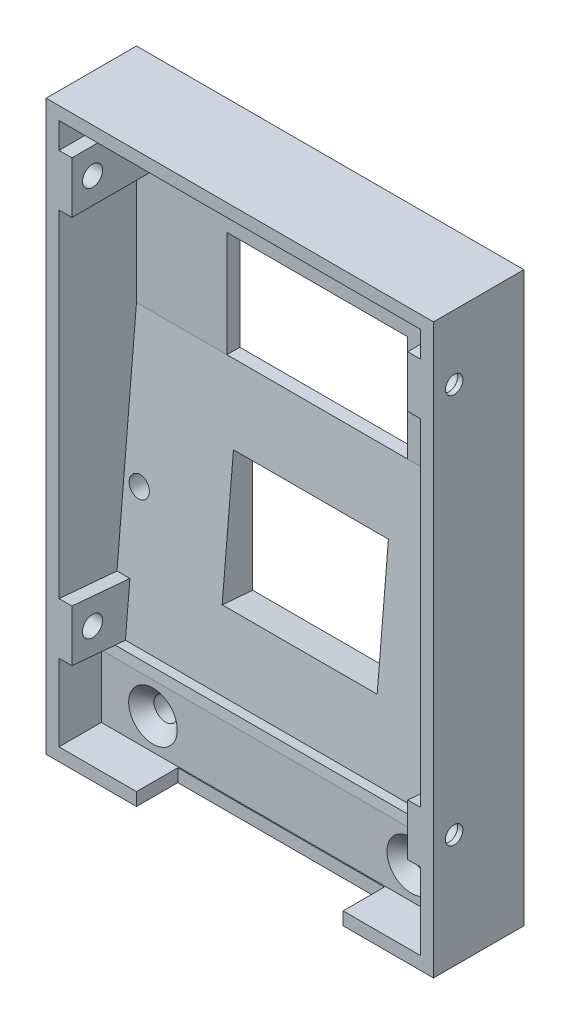
SolidWorks part; units mm, degrees
ref_plane "Přední rovina" through (0, 0, 0) normal (0, 0, 1) x (1, 0, 0)
ref_plane "Horní rovina" through (0, 0, 0) normal (0, 1, 0) x (1, 0, 0)
ref_plane "Pravá rovina" through (0, 0, 0) normal (1, 0, 0) x (0, 0, -1)
sketch "Skica1" plane through (0, 0, 0) normal (0, 0, 1) x (1, 0, 0)
  line L0 (-17.5, 35) -> (-17.5, -35)
  line L1 (-37.5, 55) -> (37.5, 55)
  line L2 (-37.5, 55) -> (-37.5, -55)
  line L3 (-37.5, -55) -> (37.5, -55)
  line L4 (37.5, 55) -> (37.5, -55)
  line L5 (-37.5, 55) -> (37.5, -55) construction
  line L6 (-37.5, -55) -> (37.5, 55) construction
  line L7 (-17.5, -35) -> (17.5, -35)
  line L8 (17.5, 35) -> (17.5, -35)
  line L9 (-17.5, 35) -> (17.5, 35)
  point P0 (0, 0)
  dimension "D1" = 75
  dimension "D2" = 110
  dimension "D3" = 20
extrude "Přidat vysunutím1" add sketch "Skica1" along normal blind 2.5
sketch "Skica2" plane through (0, 0, 2.5) normal (0, 0, 1) x (1, 0, 0)
  line L0 (-35, -52.5) -> (35, -52.5)
  line L1 (-37.5, 55) -> (37.5, 55)
  line L2 (-37.5, 55) -> (-37.5, -55)
  line L3 (-37.5, -55) -> (37.5, -55)
  line L4 (37.5, 55) -> (37.5, -55)
  line L5 (-37.5, 55) -> (37.5, -55) construction
  line L6 (-37.5, -55) -> (37.5, 55) construction
  line L7 (35, 52.5) -> (35, -52.5)
  line L8 (-35, 52.5) -> (35, 52.5)
  line L9 (-35, 52.5) -> (-35, -52.5)
  point P0 (0, 0)
  dimension "D1" = 2.5
extrude "Přidat vysunutím2" add sketch "Skica2" along normal blind 15
sketch "Skica3" plane through (35, 0, 0) normal (-1, 0, 0) x (0, 0, 1)
  line L0 (2.5, -52.5) -> (2.5, 14.5)
  line L1 (2.5, -52.5) -> (2.5, 52.5) construction
  line L2 (2.5, 14.5) -> (8.3617, -52.5)
  line L3 (17.5, -52.5) -> (2.5, -52.5) construction
  line L4 (8.3617, -52.5) -> (2.5, -52.5)
  dimension "D1" = 67
  dimension "D2" = 5
extrude "Přidat vysunutím3" add sketch "Skica3" along normal up to next
sketch "Skica4" plane through (0, 0, 2.5) normal (0, 0, -1) x (-1, 0, 0)
  line L0 (-17.5, 14.5) -> (17.5, 14.5)
  line L1 (17.5, 14.5) -> (17.5, -35)
  line L2 (17.5, -35) -> (-17.5, -35)
  line L3 (-17.5, -35) -> (-17.5, 14.5)
extrude "Přidat vysunutím4" add sketch "Skica4" along normal up to surface (2.5 mm away) up to face at (0, 0, 0)
sketch "Skica5" plane through (0, 0.3272, 3.74) normal (0, 0.0872, 0.9962) x (1, 0, 0)
  line L0 (35, -41.029) -> (-35, -41.029)
  line L1 (35, -53.029) -> (35, 14.2269) construction
  line L2 (-35, 14.2269) -> (-35, -53.029) construction
  line L4 (35, -41.029) -> (-35, -41.029)
  line L5 (35, -41.029) -> (35, -39.029)
  line L6 (35, -39.029) -> (-35, -39.029)
  line L7 (-35, -41.029) -> (-35, -39.029)
  line M3 (-35, 14.2269) -> (-35, -53.029)
  line M5 (35, -53.029) -> (35, 14.2269)
  dimension "D1" = 12
  dimension "D2" = 2
extrude "Přidat vysunutím5" add sketch "Skica5" along normal blind 2 contours L6 L0 M5 M3
ref_plane "Rovina1" through (0, 0, 8.75) normal (0, 0, -1) x (-1, 0, 0)
sketch "Skica7" plane through (35, 0, 0) normal (-1, 0, 0) x (0, 0, 1)
  line L0 (9.3083, -52.5) -> (9.3083, 14.5)
  line L1 (17.5, -52.5) -> (8.3617, -52.5) construction
  line L2 (9.3083, 14.5) -> (2.5, 14.5)
  line L3 (2.5, 14.5) -> (8.3617, -52.5)
  line L4 (8.3617, -52.5) -> (9.3083, -52.5)
ref_plane "Rovina2" through (0, 0, 0) normal (1, 0, 0) x (0, 0, -1)
sketch "Skica9" plane through (35, 0, 0) normal (-1, 0, 0) x (0, 0, 1)
  line L0 (9.3083, -52.5) -> (9.3083, -40.3714)
  line L1 (9.3083, -40.3714) -> (7.3159, -40.5457)
  line L2 (7.3159, -40.5457) -> (8.3617, -52.5)
  line L3 (8.3617, -52.5) -> (9.3083, -52.5)
extrude "Přidat vysunutím7" add sketch "Skica9" along normal through all
sketch "Skica10" plane through (0, 0, 9.3083) normal (0, 0, 1) x (1, 0, 0)
  line L0 (35, -52.5) -> (35, -40.3714)
  line L1 (35, -40.3714) -> (35, -46.4357)
  line L2 (35, -46.4357) -> (-35, -46.4357)
  line L3 (-35, -52.5) -> (-35, -40.3714) construction
  point P4 (25, -46.4357)
  point P9 (-25, -46.4357)
  dimension "D1" = 10
  dimension "D2" = 10
hole_wizard "Kuželové zahloubení pro M4 šroubu se zápustnou hlavou plochou1" positions "Skica11" profile "Skica12" countersink size "M4" standard "DIN" end condition through all
sketch "Skica11" plane through (0, 0, 9.3083) normal (0, 0, 1) x (1, 0, 0)
  point P0 (25, -46.4357)
  point P3 (-25, -46.4357)
sketch "Skica12" plane through (25, -46.4357, 9.3083) normal (1, 0, 0) x (0, -1, 0)
  line L0 (0, 0) -> (0, 9.3083)
  line L1 (0, 9.3083) -> (2.25, 9.3083)
  line L2 (2.25, 9.3083) -> (2.25, 2.45)
  line L3 (2.25, 2.45) -> (4.7, 0)
  line L5 (4.7, 0) -> (0, 0)
  line L6 (-2.25, 2.45) -> (-4.7, 0) construction
  line L11 (0, -6.35) -> (0, 107.95) construction
  dimension "Průměr díry skrz" = 4.5
  dimension "Hloubka díry skrz" = 9.3083
  dimension "Průměr blíz. kuž. zahloubení" = 9.4
  dimension "Úhel blíz. kuž. zahloubení" = 90
sketch "Skica13" plane through (0, 0, 2.5) normal (0, 0, 1) x (1, 0, 0)
  line L0 (-35, 42.5) -> (35, 42.5)
  line L1 (-35, 52.5) -> (-35, 14.5) construction
  line L2 (35, 14.5) -> (35, 52.5) construction
  point P6 (25, 42.5)
  point P7 (-25, 42.5)
  dimension "D1" = 10
  dimension "D2" = 10
  dimension "D3" = 10
hole_wizard "Kuželové zahloubení pro M4 šroubu se zápustnou hlavou plochou2" positions "Skica14" profile "Skica15" countersink size "M4" standard "DIN" end condition through all
sketch "Skica14" plane through (0, 0, 2.5) normal (0, 0, 1) x (1, 0, 0)
  point P0 (25, 42.5)
  point P3 (-25, 42.5)
sketch "Skica15" plane through (25, 42.5, 2.5) normal (1, 0, 0) x (0, -1, 0)
  line L0 (0, 0) -> (0, 2.5)
  line L1 (0, 2.5) -> (2.25, 2.5)
  line L2 (2.25, 2.5) -> (2.25, 2.45)
  line L3 (2.25, 2.45) -> (4.7, 0)
  line L5 (4.7, 0) -> (0, 0)
  line L6 (-2.25, 2.45) -> (-4.7, 0) construction
  line L11 (0, -6.35) -> (0, 107.95) construction
  dimension "Průměr díry skrz" = 4.5
  dimension "Hloubka díry skrz" = 2.5
  dimension "Průměr blíz. kuž. zahloubení" = 9.4
  dimension "Úhel blíz. kuž. zahloubení" = 90
sketch "Skica16" plane through (0, 0.3272, 3.74) normal (0, 0.0872, 0.9962) x (1, 0, 0)
  line L0 (35, -14.029) -> (-35, -14.029)
  line L1 (35, -39.029) -> (35, 14.2269) construction
  line L2 (-35, 14.2269) -> (-35, -39.029) construction
  point P6 (32, -14.029)
  point P7 (-32, -14.029)
  dimension "D1" = 25
  dimension "D2" = 3
  dimension "D3" = 3
hole_wizard "Díry pro kolík, velikost mm1" positions "Skica17" profile "Skica18" hole size "Ø4.0" standard "DIN"
sketch "Skica17" plane through (0, 0.3272, 3.74) normal (0, 0.0872, 0.9962) x (1, 0, 0)
  point P0 (32, -14.029)
  point P3 (-32, -14.029)
sketch "Skica18" plane through (32, -13.6484, 4.9627) normal (1, 0, 0) x (0, -0.9962, 0.0872)
  line L0 (0, 0) -> (0, 4)
  line L1 (0, 4) -> (1.95, 4)
  line L2 (1.95, 4) -> (1.95, 0)
  line L5 (1.95, 0) -> (0, 0)
  line L10 (0, 4) -> (-1.95, 4) construction
  line L11 (0, -6.35) -> (0, 107.95) construction
  dimension "Průměr díry" = 3.9
  dimension "Hloubka díry" = 4
  dimension "Úhel vrtání" = 180
sketch "Skica19" plane through (0, 0.3272, 3.74) normal (0, 0.0872, 0.9962) x (1, 0, 0)
  line L0 (0, 14.2269) -> (0, -39.029)
  line L1 (-17.5, 14.2269) -> (17.5, 14.2269) construction
  line L2 (35, -39.029) -> (-35, -39.029) construction
  line L4 (15, -24.901) -> (-15, -24.901)
  line L5 (15, -24.901) -> (15, 0.099)
  line L6 (15, 0.099) -> (-15, 0.099)
  line L7 (-15, -24.901) -> (-15, 0.099)
  line L8 (15, -24.901) -> (-15, 0.099) construction
  line L9 (15, 0.099) -> (-15, -24.901) construction
  point P6 (0, -12.401)
  dimension "D1" = 30
  dimension "D2" = 25
extrude "Odebrat vysunutím1" cut sketch "Skica19" against normal through all contours L5 L6 L7 L4
sketch "Skica20" plane through (0, -55, 0) normal (0, -1, 0) x (1, 0, 0)
  line L3 (0, 9.5) -> (-20, 9.5)
  line L4 (-20, 9.5) -> (-20, 17.5)
  line L5 (0, 9.5) -> (20, 9.5)
  line L6 (20, 9.5) -> (20, 17.5)
  line L7 (-20, 17.5) -> (20, 17.5)
  line L10 (-37.5, 17.5) -> (37.5, 17.5) construction
  line L11 (-20, 17.5) -> (20, 17.5)
  point P6 (0, 9.5)
  dimension "D1" = 20
  dimension "D2" = 20
  dimension "D3" = 9.5
extrude "Odebrat vysunutím4" cut sketch "Skica20" against normal blind 10
sketch "Skica21" plane through (-35, 0, 0) normal (1, 0, 0) x (0, 0, -1)
  line L0 (-7.1416, -38.5533) -> (-6.2733, -28.6292)
  line L1 (-2.5, 14.5) -> (-7.1416, -38.5533) construction
  line L2 (-6.2733, -28.6292) -> (-17.5, -27.647)
  line L3 (-17.5, 52.5) -> (-17.5, -52.5) construction
  line L4 (-17.5, -27.647) -> (-17.5, -37.647)
  line L5 (-17.5, -37.647) -> (-7.1416, -38.5533)
  line L6 (-2.5, 52.5) -> (-2.5, 14.5) construction
  line L7 (-17.5, 47.5) -> (-2.5, 47.5)
  line L8 (-17.5, 47.5) -> (-17.5, 37.5)
  line L9 (-17.5, 37.5) -> (-2.5, 37.5)
  line L10 (-2.5, 47.5) -> (-2.5, 37.5)
  dimension "D1" = 10
  dimension "D2" = 5
  dimension "D3" = 10
extrude "Přidat vysunutím8" add sketch "Skica21" along normal blind 2.5
mirror "Zrcadlit1" about plane through (0, 0, 0) normal (1, 0, 0) of "Přidat vysunutím8"
sketch "Skica22" plane through (-32.5, 0, 0) normal (1, 0, 0) x (0, 0, -1)
  line L0 (-17.5, -32.647) -> (-6.7074, -33.5913)
  line L1 (-17.5, -27.647) -> (-17.5, -37.647) construction
  line L2 (-7.1416, -38.5533) -> (-6.2733, -28.6292) construction
  line L3 (-17.5, 42.5) -> (-2.5, 42.5)
  line L4 (-17.5, 47.5) -> (-17.5, 37.5) construction
  line L5 (-2.5, 37.5) -> (-2.5, 47.5) construction
  point P6 (-13.5152, -32.9957)
  point P13 (-13.5, 42.5)
  dimension "D1" = 4
  dimension "D2" = 4
hole_wizard "Válcové zahloubení pro M3 šrouby s vnitřním šestihranem1" positions "Skica23" profile "Skica24" counterbore size "M3" standard "DIN"
sketch "Skica23" plane through (-32.5, 0, 0) normal (1, 0, 0) x (0, 0, -1)
  point P0 (-13.5, 42.5)
  point P3 (-13.5152, -32.9957)
sketch "Skica24" plane through (-32.5, 42.5, 13.5) normal (0, 1, 0) x (0, 0, -1)
  line L0 (0, 0) -> (0, 5)
  line L1 (0, 5) -> (1.7, 5)
  line L3 (1.7, 5) -> (1.7, 4)
  line L4 (1.7, 4) -> (1.95, 4)
  line L5 (1.95, 4) -> (1.95, 0)
  line L7 (1.95, 0) -> (0, 0)
  line L11 (0, -6.35) -> (0, 107.95) construction
  dimension "Průměr díry skrz" = 3.4
  dimension "Hloubka díry skrz" = 5
  dimension "Průměr válcového zahloubení" = 3.9
  dimension "Hloubka válcového zahloubení" = 4
mirror "Zrcadlit2" about plane through (0, 0, 0) normal (1, 0, 0) of "Válcové zahloubení pro M3 šrouby s vnitřním šestihranem1"
